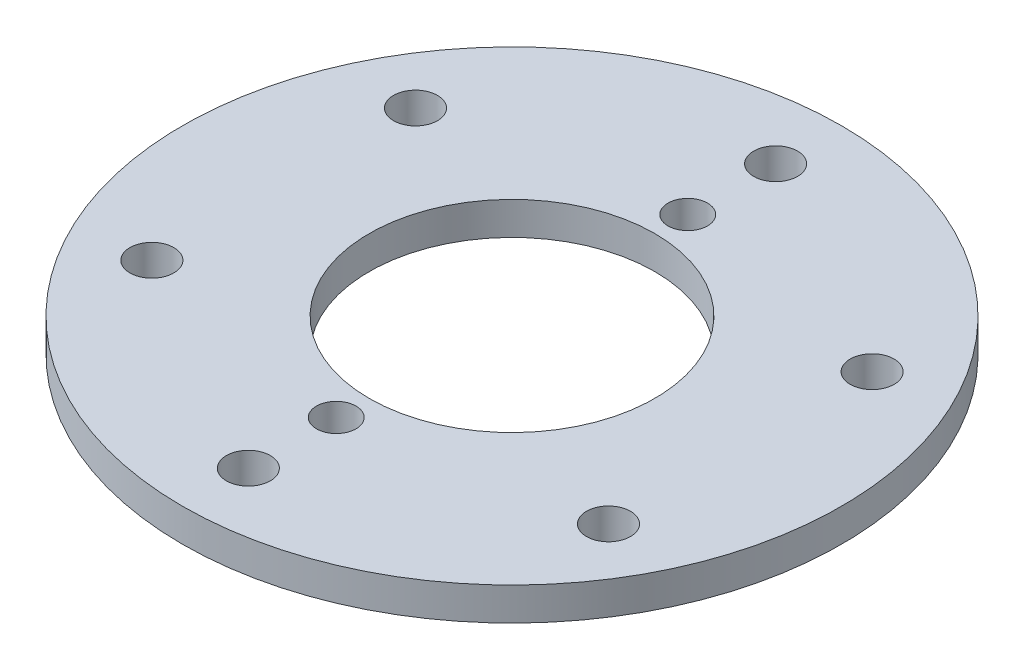
SolidWorks part; units mm, degrees
ref_plane "Front Plane" through (0, 0, 0) normal (0, 0, 1) x (1, 0, 0)
ref_plane "Top Plane" through (0, 0, 0) normal (0, 1, 0) x (1, 0, 0)
ref_plane "Right Plane" through (0, 0, 0) normal (1, 0, 0) x (0, 0, -1)
sketch "Sketch2" plane through (0, 0, 0) normal (0, 1, 0) x (1, 0, 0)
  line L0 (0, -150) -> (0, 150) construction
  line L1 (-150, 0) -> (150, 0) construction
  circle A0 centre (0, 0) radius 65
  circle A1 centre (0, 0) radius 150
  circle A2 centre (0, 0) radius 120 construction
  circle A3 centre (0, 120) radius 10
  circle A4 centre (103.923, 60) radius 10
  circle A5 centre (103.923, -60) radius 10
  circle A6 centre (0, -120) radius 10
  circle A7 centre (-103.923, -60) radius 10
  circle A8 centre (-103.923, 60) radius 10
  circle A9 centre (0, 80) radius 9
  circle A11 centre (0, -80) radius 9
  point P7 (0, 0)
  point P10 (0, 0)
  point P26 (0, 0)
  dimension "D1" = 300
  dimension "D2" = 130
  dimension "D3" = 240
  dimension "D4" = 20
  dimension "D6" = 18
  dimension "D7" = 80
  dimension "D5" = 6
extrude "Boss-Extrude1" add sketch "Sketch2" along normal blind 15
